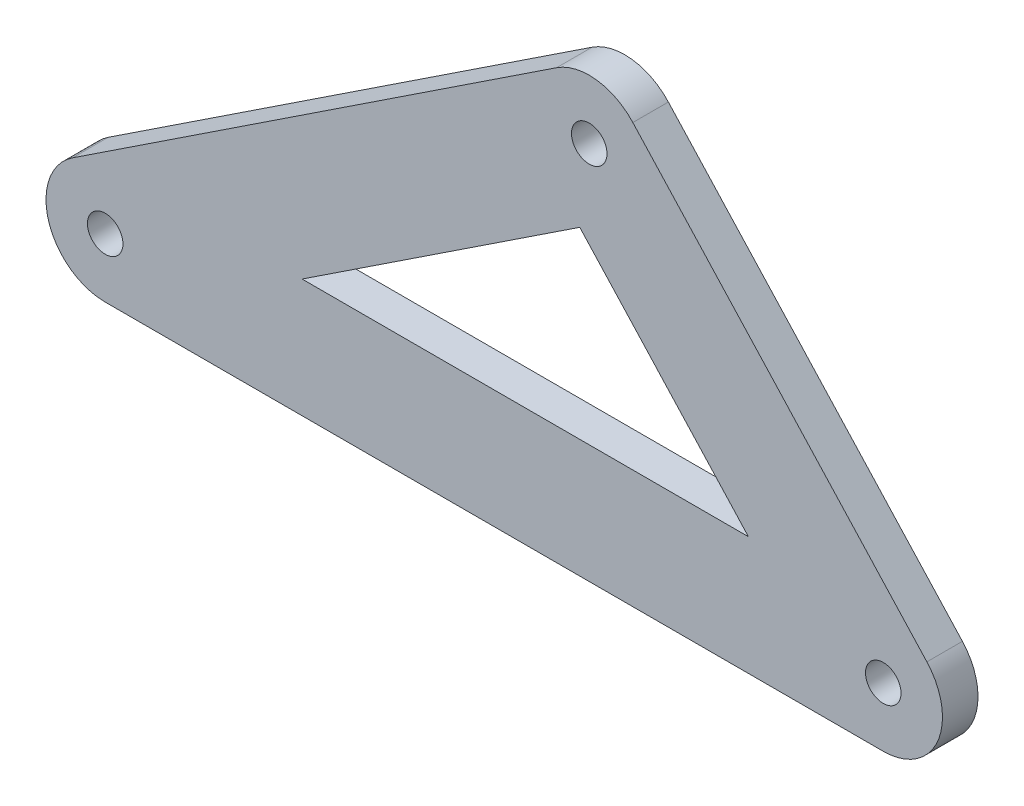
SolidWorks part; units mm, degrees
material "Acrylic (Medium-high impact)"
ref_plane "Front Plane" through (0, 0, 0) normal (0, 0, 1) x (1, 0, 0)
ref_plane "Top Plane" through (0, 0, 0) normal (0, 1, 0) x (1, 0, 0)
ref_plane "Right Plane" through (0, 0, 0) normal (1, 0, 0) x (0, 0, -1)
sketch "Sketch1" plane through (0, 0, 0) normal (0, 0, 1) x (1, 0, 0)
  line L3 (-2.7579, 4.1706) -> (38.1143, 31.1978)
  line L4 (44.5543, 30.4097) -> (69.3822, 3.3825)
  line L5 (65.7, -5) -> (0, -5)
  line L6 (40.074, 20.5051) -> (54.3174, 5)
  line L7 (54.3174, 5) -> (16.6263, 5)
  line L8 (16.6263, 5) -> (40.074, 20.5051)
  circle A0 centre (40.8721, 27.0272) radius 1.5
  circle A1 centre (0, 0) radius 1.5
  circle A2 centre (65.7, 0) radius 1.5
  arc A3 (44.5543, 30.4097) -> (38.1143, 31.1978) centre (40.8721, 27.0272) ccw
  arc A4 (0, -5) -> (-2.7579, 4.1706) centre (0, 0) cw
  arc A5 (65.7, -5) -> (69.3822, 3.3825) centre (65.7, 0) ccw
  dimension "D6" = 3
  dimension "D7" = 3
  dimension "D8" = 3
  dimension "D9" = 5
  dimension "D10" = 5
  dimension "D11" = 5
  dimension "D1" = 65.7
  dimension "D2" = 36.7
  dimension "D3" = 49
extrude "Boss-Extrude1" add sketch "Sketch1" along normal blind 3
